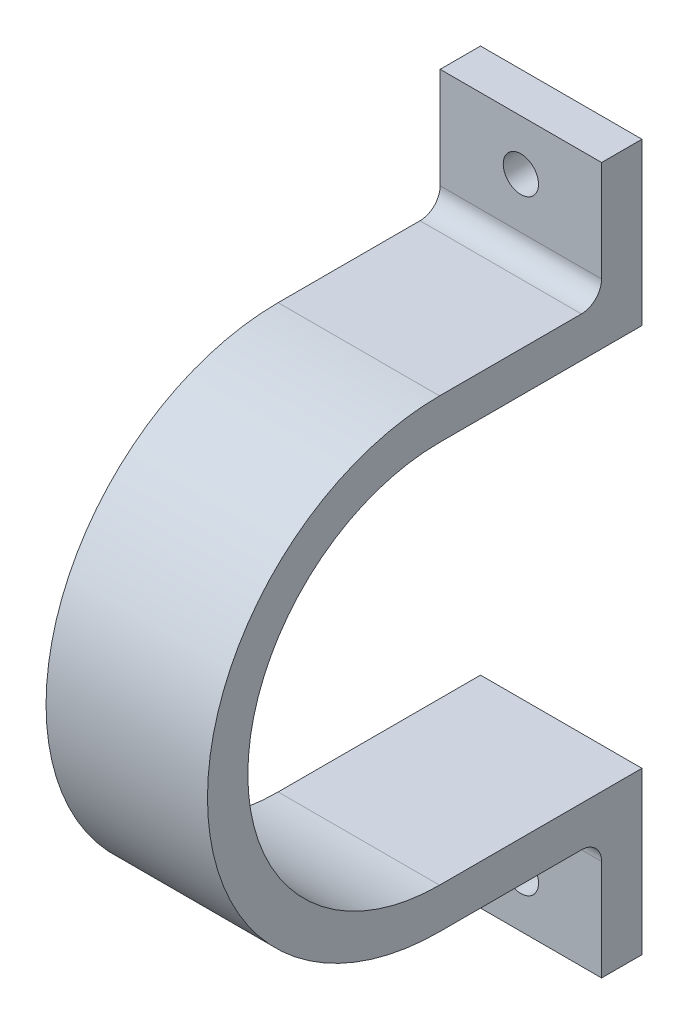
SolidWorks part; units mm, degrees
ref_plane "Front Plane" through (0, 0, 0) normal (1, 0, 0) x (0, 1, 0)
ref_plane "Top Plane" through (0, 0, 0) normal (0, 0, 1) x (0, 1, 0)
ref_plane "Right Plane" through (0, 0, 0) normal (0, 1, 0) x (-1, 0, 0)
sketch "Sketch2" plane through (0, 0, 0) normal (1, 0, 0) x (0, 1, 0)
  line L0 (0, 0) -> (0, 20.0624)
  line L1 (-38, 20.0624) -> (-38, 0)
  line L2 (-38, 0) -> (-54, 0)
  line L3 (-54, 0) -> (-54, 4)
  line L4 (-54, 4) -> (-42, 4)
  line L5 (-42, 4) -> (-42, 20.0624)
  line L6 (4, 20.0624) -> (4, 4)
  line L7 (4, 4) -> (16, 4)
  line L8 (16, 4) -> (16, 0)
  line L9 (16, 0) -> (0, 0)
  line L10 (-19, 20.0624) -> (-19, 39.0624) construction
  line L11 (-54, -0.5) -> (16, -0.5) construction
  line L12 (-31.75, -0.5) -> (-31.75, 2.5) construction
  line L13 (-31.75, 2.5) -> (-26.25, 2.5) construction
  line L14 (-26.25, 2.5) -> (-26.25, -0.5) construction
  line L15 (-29, 2.5) -> (-29, -0.5) construction
  arc A0 (0, 20.0624) -> (-38, 20.0624) centre (-19, 20.0624) ccw
  arc A1 (-42, 20.0624) -> (4, 20.0624) centre (-19, 20.0624) cw
  circle A2 centre (-19, 20.0624) radius 19 construction
  point P25 (0, 0)
  dimension "D1" = 19
  dimension "D2" = 4
  dimension "D3" = 70
  dimension "D4" = 4
  dimension "D5" = 5.5
  dimension "D6" = 3
  dimension "D7" = 10
  dimension "D8" = 1
extrude "Boss-Extrude1" add sketch "Sketch2" along normal blind 16
sketch "Sketch3" plane through (0, 0, 0) normal (0, 0, -1) x (1, 0, 0)
  line L0 (0, 19) -> (16, 19) construction
  line L1 (0, 38) -> (0, 0) construction
  line L2 (16, 0) -> (16, 38) construction
  line L3 (8, 54) -> (8, -16) construction
  line L4 (16, 54) -> (0, 54) construction
  line L5 (16, -16) -> (0, -16) construction
  circle A0 centre (8, 49) radius 1.75
  circle A1 centre (8, -11) radius 1.75
  dimension "D2" = 3.5
  dimension "D1" = 30
extrude "Cut-Extrude1" cut sketch "Sketch3" against normal up to next
fillet "Fillet1" radius 2 2 edges at (8, 4, 4) (8, -42, 4)
